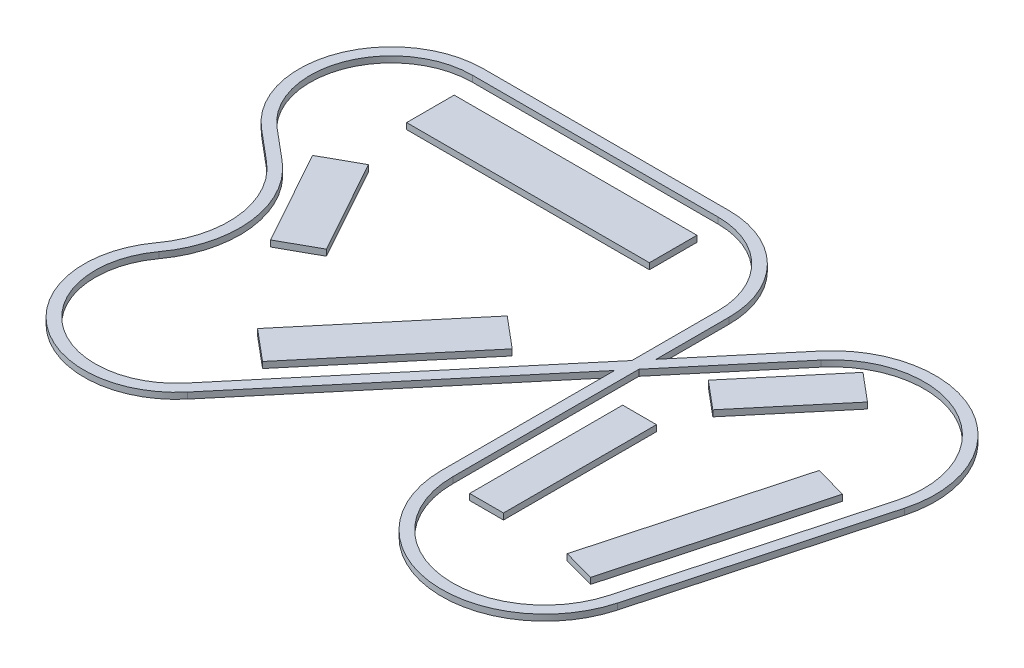
SolidWorks part; units mm, degrees
ref_plane "Front Plane" through (0, 0, 0) normal (0, 0, 1) x (1, 0, 0)
ref_plane "Top Plane" through (0, 0, 0) normal (0, 1, 0) x (1, 0, 0)
ref_plane "Right Plane" through (0, 0, 0) normal (1, 0, 0) x (0, 0, -1)
sketch "Sketch1" plane through (0, 0, 0) normal (0, 1, 0) x (1, 0, 0)
  line L3 (-200, 350) -> (200, 350)
  line L5 (-296.4181, 85.0933) -> (-245.4784, 42.3498)
  line L8 (14.9067, -346.4181) -> (485.0933, 213.9285)
  line L10 (350, 200) -> (350, -250)
  line L11 (744.7376, 78.1271) -> (644.7376, -289.3833)
  arc A0 (-200, 350) -> (-296.4181, 85.0933) centre (-200, 200) ccw
  arc A1 (-245.4784, 42.3498) -> (-220.9483, -161.2784) centre (-341.8965, -72.5569) cw
  arc A2 (-220.9483, -161.2784) -> (14.9067, -346.4181) centre (-100, -250) ccw
  arc A3 (350, 200) -> (200, 350) centre (200, 200) ccw
  arc A4 (485.0933, 213.9285) -> (744.7376, 78.1271) centre (600, 117.5104) cw
  arc A5 (644.7376, -289.3833) -> (350, -250) centre (500, -250) cw
  dimension "D1" = 150
  dimension "D3" = 150
  dimension "D5" = 150
  dimension "D6" = 150
  dimension "D12" = 150
  dimension "D14" = 150
  dimension "D2" = 200
  dimension "D4" = 245.4784
  dimension "D7" = 250
  dimension "D8" = 296.4181
  dimension "D9" = 200
  dimension "D10" = 400
  dimension "D11" = 600
  dimension "D13" = 450
sketch "Sketch3" plane through (0, 0, 0) normal (0, 1, 0) x (1, 0, 0)
  line L0 (-200, 332) -> (200, 332)
  line L1 (-284.848, 98.8821) -> (-233.9082, 56.1386)
  line L2 (-296.4181, 85.0933) -> (-245.4784, 42.3498) construction
  line L3 (1.1179, -334.848) -> (471.3045, 225.4987)
  line L4 (14.9067, -346.4181) -> (485.0933, 213.9285) construction
  line L5 (332, 200) -> (332, -250)
  line L6 (-200, 350) -> (200, 350) construction
  line L7 (350, 200) -> (350, -250) construction
  line L8 (762.1061, 73.4011) -> (662.1061, -294.1092)
  line L9 (744.7376, 78.1271) -> (644.7376, -289.3833) construction
  arc A0 (-200, 332) -> (-284.848, 98.8821) centre (-200, 200) ccw
  arc A1 (-206.4345, -171.925) -> (-233.9082, 56.1386) centre (-341.8965, -72.5569) ccw
  arc A3 (-206.4345, -171.925) -> (1.1179, -334.848) centre (-100, -250) ccw
  arc A4 (332, 200) -> (200, 332) centre (200, 200) ccw
  arc A5 (-200, 350) -> (-296.4181, 85.0933) centre (-200, 200) ccw construction
  arc A6 (762.1061, 73.4011) -> (471.3045, 225.4987) centre (600, 117.5104) ccw
  arc A7 (332, -250) -> (662.1061, -294.1092) centre (500, -250) ccw
  arc A8 (744.7376, 78.1271) -> (485.0933, 213.9285) centre (600, 117.5104) ccw construction
  dimension "D1" = 18
  dimension "D2" = 18
sketch "Sketch4" plane through (0, 0, 0) normal (0, 1, 0) x (1, 0, 0)
  line L0 (1.1179, -334.848) -> (471.3045, 225.4987) construction
  line L2 (332, 200) -> (332, -250) construction
  line L3 (350, 200) -> (350, -250) construction
  line L4 (-284.848, 98.8821) -> (-233.9082, 56.1386) construction
  line L5 (-296.4181, 85.0933) -> (-245.4784, 42.3498) construction
  line L6 (-200, 350) -> (200, 350) construction
  line L7 (-200, 332) -> (200, 332) construction
  line L8 (1.1179, -334.848) -> (332, 59.482)
  line L9 (14.9067, -346.4181) -> (485.0933, 213.9285) construction
  line L10 (332, 200) -> (332, 59.482)
  line L11 (350, 200) -> (350, 52.9305)
  line L12 (-284.848, 98.8821) -> (-233.9082, 56.1386)
  line L13 (-296.4181, 85.0933) -> (-245.4784, 42.3498)
  line L14 (-200, 350) -> (200, 350)
  line L15 (-200, 332) -> (200, 332)
  line L16 (14.9067, -346.4181) -> (350, 52.9305)
  arc A0 (350, 200) -> (200, 350) centre (200, 200) ccw construction
  arc A1 (332, 200) -> (200, 332) centre (200, 200) ccw construction
  arc A2 (-220.9483, -161.2784) -> (14.9067, -346.4181) centre (-100, -250) ccw construction
  arc A3 (-206.4345, -171.925) -> (1.1179, -334.848) centre (-100, -250) ccw construction
  arc A4 (-220.9483, -161.2784) -> (-245.4784, 42.3498) centre (-341.8965, -72.5569) ccw construction
  arc A5 (-206.4345, -171.925) -> (-233.9082, 56.1386) centre (-341.8965, -72.5569) ccw construction
  arc A6 (-200, 332) -> (-284.848, 98.8821) centre (-200, 200) ccw construction
  arc A7 (-200, 350) -> (-296.4181, 85.0933) centre (-200, 200) ccw construction
  arc A8 (350, 200) -> (200, 350) centre (200, 200) ccw
  arc A9 (332, 200) -> (200, 332) centre (200, 200) ccw
  arc A10 (-220.9483, -161.2784) -> (14.9067, -346.4181) centre (-100, -250) ccw
  arc A11 (-206.4345, -171.925) -> (1.1179, -334.848) centre (-100, -250) ccw
  arc A12 (-220.9483, -161.2784) -> (-245.4784, 42.3498) centre (-341.8965, -72.5569) ccw
  arc A13 (-206.4345, -171.925) -> (-233.9082, 56.1386) centre (-341.8965, -72.5569) ccw
  arc A14 (-200, 332) -> (-284.848, 98.8821) centre (-200, 200) ccw
  arc A15 (-200, 350) -> (-296.4181, 85.0933) centre (-200, 200) ccw
extrude "Boss-Extrude1" add sketch "Sketch4" along normal blind 10
sketch "Sketch5" plane through (0, 0, 0) normal (0, 1, 0) x (1, 0, 0)
  line L1 (762.1061, 73.4011) -> (662.1061, -294.1092) construction
  line L2 (14.9067, -346.4181) -> (485.0933, 213.9285) construction
  line L3 (350, 200) -> (350, -250) construction
  line L4 (332, 200) -> (332, -250) construction
  line L6 (762.1061, 73.4011) -> (662.1061, -294.1092)
  line L7 (332, 31.479) -> (350, 52.9305)
  line L8 (350, 80.9336) -> (350, 52.9305)
  line L9 (332, 31.479) -> (332, -250)
  line L10 (1.1179, -334.848) -> (471.3045, 225.4987) construction
  line L11 (350, 80.9336) -> (471.3045, 225.4987)
  arc A0 (762.1061, 73.4011) -> (471.3045, 225.4987) centre (600, 117.5104) ccw construction
  arc A2 (332, -250) -> (662.1061, -294.1092) centre (500, -250) ccw construction
  arc A4 (762.1061, 73.4011) -> (471.3045, 225.4987) centre (600, 117.5104) ccw
  arc A6 (332, -250) -> (662.1061, -294.1092) centre (500, -250) ccw
extrude "Boss-Extrude4" add sketch "Sketch5" along normal blind 10
sketch "Sketch6" plane through (0, 0, 0) normal (0, 1, 0) x (1, 0, 0)
  line L0 (744.7376, 78.1271) -> (644.7376, -289.3833) construction
  line L1 (350, 200) -> (350, -250) construction
  line L2 (14.9067, -346.4181) -> (485.0933, 213.9285) construction
  line L3 (744.7376, 78.1271) -> (644.7376, -289.3833)
  line L4 (350, 52.9305) -> (350, -250)
  line L5 (350, 52.9305) -> (485.0933, 213.9285)
  arc A0 (350, -250) -> (644.7376, -289.3833) centre (500, -250) ccw construction
  arc A1 (744.7376, 78.1271) -> (485.0933, 213.9285) centre (600, 117.5104) ccw construction
  arc A2 (350, -250) -> (644.7376, -289.3833) centre (500, -250) ccw
  arc A3 (744.7376, 78.1271) -> (485.0933, 213.9285) centre (600, 117.5104) ccw
extrude "Cut-Extrude1" cut sketch "Sketch6" along normal through all
sketch "Sketch7" plane through (0, 0, 0) normal (0, 1, 0) x (1, 0, 0)
  line L0 (32.748, -242.4097) -> (218.1804, -21.4199)
  line L1 (-186.7697, 289.1018) -> (208.3994, 289.1018)
  line L2 (-186.7697, 289.1018) -> (-186.7697, 211.6813)
  line L3 (-186.7697, 211.6813) -> (208.3994, 211.6813)
  line L4 (208.3994, 289.1018) -> (208.3994, 211.6813)
  line L5 (32.748, -242.4097) -> (-17.7382, -200.0467)
  line L6 (218.1804, -21.4199) -> (167.6942, 20.943)
  line L7 (-17.7382, -200.0467) -> (167.6942, 20.943)
  line L8 (604.0781, -279.6461) -> (691.775, 42.6492)
  line L9 (604.0781, -279.6461) -> (551.7072, -265.3959)
  line L10 (691.775, 42.6492) -> (639.4041, 56.8994)
  line L11 (551.7072, -265.3959) -> (639.4041, 56.8994)
  line L12 (1.1179, -334.848) -> (332, 59.482) construction
  line L13 (387.3666, -10.8374) -> (442.4345, -10.8374)
  line L14 (387.3666, -10.8374) -> (387.3666, -259.8876)
  line L15 (387.3666, -259.8876) -> (442.4345, -259.8876)
  line L16 (442.4345, -10.8374) -> (442.4345, -259.8876)
  line L17 (644.7376, -289.3833) -> (744.7376, 78.1271) construction
  line L18 (-216.9806, 88.8551) -> (-132.1692, -64.5303)
  line L19 (-216.9806, 88.8551) -> (-158.4243, 121.2326)
  line L20 (-132.1692, -64.5303) -> (-73.6129, -32.1528)
  line L21 (-158.4243, 121.2326) -> (-73.6129, -32.1528)
  line L22 (536.7807, 230.9393) -> (421.9288, 94.0641)
  line L23 (536.7807, 230.9393) -> (582.2085, 192.8209)
  line L24 (421.9288, 94.0641) -> (467.3566, 55.9458)
  line L25 (582.2085, 192.8209) -> (467.3566, 55.9458)
  line L26 (485.0933, 213.9285) -> (350, 52.9305) construction
extrude "Boss-Extrude5" add sketch "Sketch7" along normal blind 10 separate body
